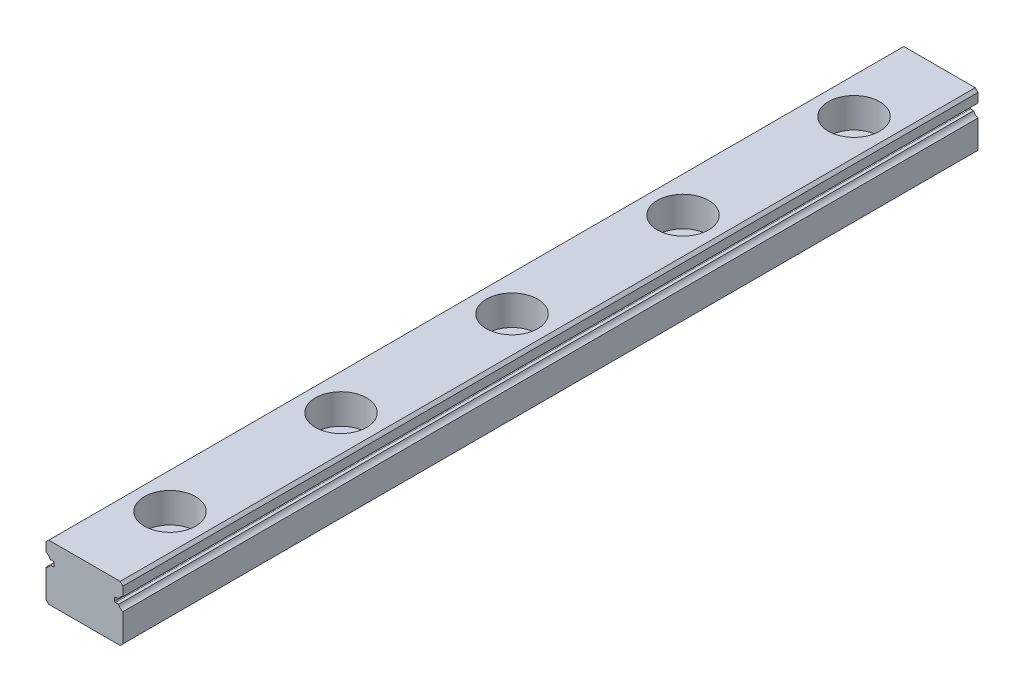
SolidWorks part; units mm, degrees
ref_plane "前视基准面" through (0, 0, 0) normal (0, 0, 1) x (1, 0, 0)
ref_plane "上视基准面" through (0, 0, 0) normal (0, 1, 0) x (1, 0, 0)
ref_plane "右视基准面" through (0, 0, 0) normal (1, 0, 0) x (0, 0, -1)
sketch "草图1" plane through (0, 0, 0) normal (0, 0, 1) x (1, 0, 0)
  line L0 (-1000, 0) -> (0, 0) construction
  line L1 (0, 0) -> (0, 4.2699) construction
  line L15 (-4.5, -2.9053) -> (-4.5, -6.1753)
  line L16 (-4.5, -6.1753) -> (-4.1747, -6.5005)
  line L19 (-4.1747, 0) -> (-4.5, -0.3253)
  line L20 (-4.5, -0.3253) -> (-4.5, -1.3953)
  line L23 (-3.5401, -1.9703) -> (-3.5401, -2.3303)
  line L27 (-4.1747, -6.5005) -> (0, -6.5005)
  line L37 (-3.6301, -1.8803) -> (-3.9901, -1.8803)
  line L38 (-3.6301, -2.4203) -> (-3.9901, -2.4203)
  line L40 (-4.1747, 0) -> (0, 0)
  line L41 (4.1747, 0) -> (0, 0)
  line L42 (3.6301, -2.4203) -> (3.9901, -2.4203)
  line L43 (3.6301, -1.8803) -> (3.9901, -1.8803)
  line L44 (4.1747, -6.5005) -> (0, -6.5005)
  line L45 (3.5401, -1.9703) -> (3.5401, -2.3303)
  line L46 (4.5, -0.3253) -> (4.5, -1.3953)
  line L47 (4.1747, 0) -> (4.5, -0.3253)
  line L48 (4.5, -6.1753) -> (4.1747, -6.5005)
  line L49 (4.5, -2.9053) -> (4.5, -6.1753)
  arc A1 (-4.5, -2.9053) -> (-3.9901, -2.4203) centre (-4.7325, -2.1503) ccw
  arc A2 (-3.5401, -1.9703) -> (-3.6301, -1.8803) centre (-3.6301, -1.9703) ccw
  arc A3 (-3.6301, -2.4203) -> (-3.5401, -2.3303) centre (-3.6301, -2.3303) ccw
  arc A4 (3.6301, -2.4203) -> (3.5401, -2.3303) centre (3.6301, -2.3303) cw
  arc A5 (3.5401, -1.9703) -> (3.6301, -1.8803) centre (3.6301, -1.9703) cw
  arc A6 (4.5, -2.9053) -> (3.9901, -2.4203) centre (4.7325, -2.1503) cw
  arc A7 (-3.9901, -1.8803) -> (-4.5, -1.3953) centre (-4.7325, -2.1503) ccw
  arc A8 (3.9901, -1.8803) -> (4.5, -1.3953) centre (4.7325, -2.1503) cw
  point P2 (-3.8101, -1.8803)
  point P16 (-3.8101, -2.4203)
  dimension "D9" = 1.51
  dimension "D10" = 1.58
  dimension "D13" = 0.18
  dimension "D14" = 0.09
  dimension "D6" = 0.09
  dimension "D7" = 0.79
  dimension "D16" = 135
  dimension "D22" = 0.54
  dimension "D2" = 9
  dimension "D3" = 135
  dimension "D4" = 135
  dimension "D5" = 0.46
  dimension "D8" = 1.07
  dimension "D11" = 0.54
  dimension "D12" = 0.27
  dimension "D15" = 0.36
  dimension "D17" = 0.46
  dimension "D18" = 135
  dimension "D19" = 9
  dimension "D20" = 3.27
  dimension "D21" = 0.36
  dimension "D23" = 0.27
extrude "凸台-拉伸1" add sketch "草图1" along normal blind 100
sketch "草图6" plane through (0, 0, 0) normal (0, 1, 0) x (1, 0, 0)
  line L0 (4.1747, -100) -> (-4.1747, -100) construction
  point P0 (0, -90)
  dimension "D1" = 10
hole_wizard "M2 六角头螺栓的柱形沉头孔1" positions "草图6" profile "草图4" counterbore size "M2" standard "GB" end condition up to next
sketch "草图4" plane through (0, 0, 90) normal (1, 0, 0) x (0, 0, 1)
  line L0 (0, 0) -> (0, 6.5005)
  line L1 (0, 6.5005) -> (1.2, 6.5005)
  line L3 (1.2, 6.5005) -> (1.2, 3.5)
  line L4 (1.2, 3.5) -> (3, 3.5)
  line L5 (3, 3.5) -> (3, 0)
  line L7 (3, 0) -> (0, 0)
  line L11 (0, -6.35) -> (0, 107.95) construction
  dimension "通孔孔直径" = 2.4
  dimension "通孔孔深度" = 6.5005
  dimension "柱形沉头孔直径" = 6
  dimension "柱形沉头孔深度" = 3.5
pattern_linear "阵列(线性)1" count 5 spacing 20 along (0, 0, -1) of "M2 六角头螺栓的柱形沉头孔1"
